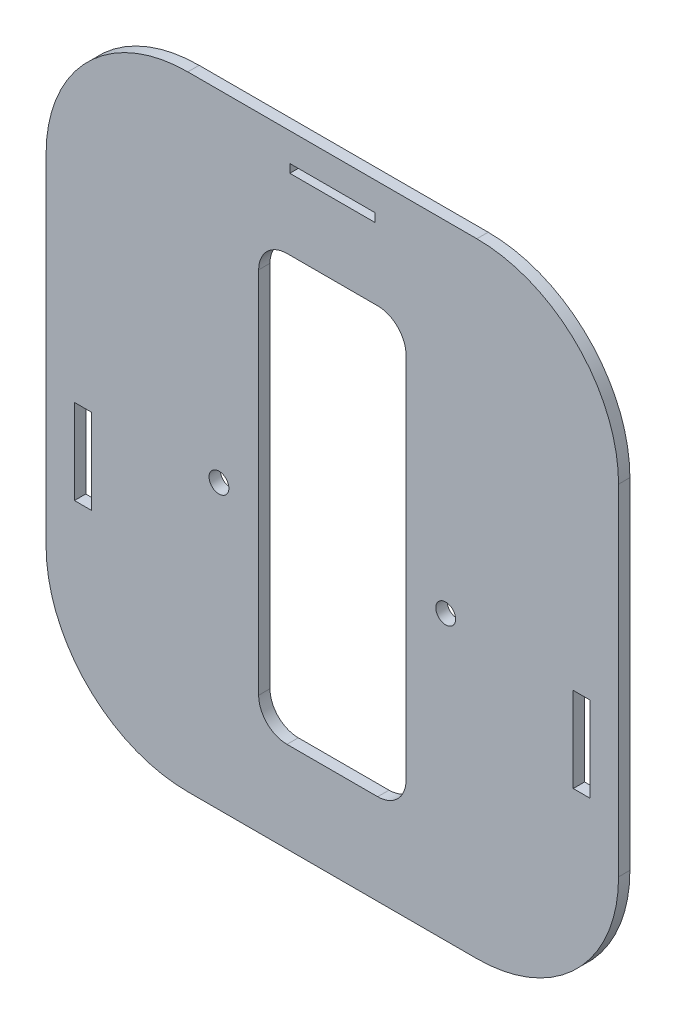
SolidWorks part; units mm, degrees
material "PE Low/Medium Density"
ref_plane "Front Plane" through (0, 0, 0) normal (0, 0, 1) x (1, 0, 0)
ref_plane "Top Plane" through (0, 0, 0) normal (0, 1, 0) x (1, 0, 0)
ref_plane "Right Plane" through (0, 0, 0) normal (1, 0, 0) x (0, 0, -1)
sketch "Sketch1" plane through (0, 0, 0) normal (0, 0, 1) x (1, 0, 0)
  line L0 (48, 82.1) -> (37, 82.1) construction
  line L1 (-8, 87.1) -> (93, 87.1)
  line L2 (-8, 87.1) -> (-8, -22.9)
  line L3 (-8, -22.9) -> (93, -22.9)
  line L4 (93, 87.1) -> (93, -22.9)
  line L5 (88, 11.6) -> (88, -12.4009) construction
  line L6 (-3, 26.6) -> (-3, 40.6) construction
  dimension "D1" = 5
  dimension "D2" = 5
  dimension "D3" = 5
  dimension "D4" = 110
extrude "Boss-Extrude1" add sketch "Sketch1" along normal blind 2
sketch "Sketch3" plane through (0, 0, 2) normal (0, 0, 1) x (1, 0, 0)
  line L1 (35, 82.1) -> (50, 82.1)
  line L2 (35, 82.1) -> (35, 80.6)
  line L3 (35, 80.6) -> (50, 80.6)
  line L4 (50, 82.1) -> (50, 80.6)
  line L5 (-3, 26.6) -> (0, 26.6)
  line L6 (-3, 26.6) -> (-3, 11.6)
  line L7 (-3, 11.6) -> (0, 11.6)
  line L8 (0, 26.6) -> (0, 11.6)
  line L9 (85, 26.6) -> (88, 26.6)
  line L10 (85, 26.6) -> (85, 11.6)
  line L11 (85, 11.6) -> (88, 11.6)
  line L12 (88, 26.6) -> (88, 11.6)
extrude "Cut-Extrude1" cut sketch "Sketch3" against normal through all
sketch "Sketch4" plane through (0, 0, 2) normal (0, 0, 1) x (1, 0, 0)
  line L0 (22.5, 27.1) -> (62.5, 27.1) construction
  line L1 (42.5, 27.1) -> (42.5, -22.9) construction
  line L2 (-8, -22.9) -> (93, -22.9) construction
  circle A0 centre (22.5, 27.1) radius 1.75
  circle A1 centre (62.5, 27.1) radius 1.75
  dimension "D2" = 3.5
  dimension "D1" = 40
  dimension "D3" = 50
fillet "Fillet2" radius 25 4 edges at (93, 87.1, 1) (93, -22.9, 1) (-8, -22.9, 1) (-8, 87.1, 1)
sketch "Sketch9" plane through (0, 0, 2) normal (0, 0, 1) x (1, 0, 0)
  line L0 (-8, 62.1) -> (-8, 2.1) construction
  line L1 (29.5, 68.1) -> (55.5, 68.1)
  line L2 (29.5, 68.1) -> (29.5, -6.9)
  line L3 (29.5, -6.9) -> (55.5, -6.9)
  line L4 (55.5, 68.1) -> (55.5, -6.9)
  line L5 (93, 2.1) -> (93, 62.1) construction
  line L6 (17, -22.9) -> (68, -22.9) construction
  dimension "D1" = 37.5
  dimension "D2" = 37.5
  dimension "D4" = 16
  dimension "D3" = 75
extrude "Cut-Extrude2" cut sketch "Sketch9" against normal through all
fillet "Fillet3" radius 5 4 edges at (29.5, -6.9, 1) (55.5, -6.9, 1) (55.5, 68.1, 1) (29.5, 68.1, 1)
extrude "Cut-Extrude3" cut sketch "Sketch4" against normal blind 10
